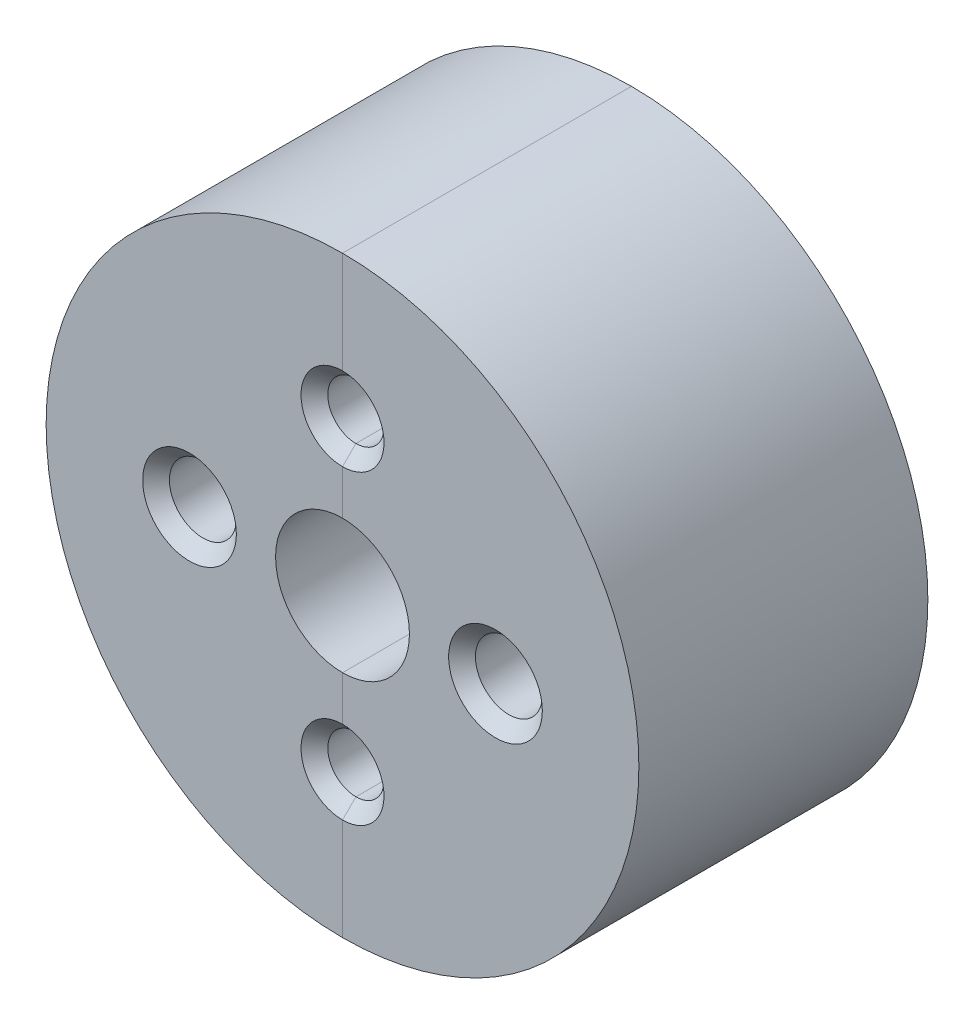
SolidWorks part; units mm, degrees
material "AISI 8620, Normalized steel"
ref_plane "Front Plane" through (0, 0, 0) normal (0, 0, 1) x (1, 0, 0)
ref_plane "Top Plane" through (0, 0, 0) normal (0, 1, 0) x (1, 0, 0)
ref_plane "Right Plane" through (0, 0, 0) normal (1, 0, 0) x (0, 0, -1)
sketch "Sketch1" plane through (0, 0, 0) normal (0, 0, 1) x (1, 0, 0)
  circle A0 centre (0, 0) radius 22.1425
  dimension "D1" = 44.2849
extrude "Boss-Extrude1" add sketch "Sketch1" along normal blind 21.59 contours A0
chamfer "Chamfer1" [suppressed] distance 2 angle 45
sketch "Sketch2" plane through (0, 0, 0) normal (0, 0, -1) x (-1, 0, 0)
  circle A0 centre (0, 0) radius 22.1425 construction
  circle A1 centre (0, 0) radius 22.1425
sketch "Sketch4" plane through (0, 0, 0) normal (0, 0, -1) x (-1, 0, 0)
  circle A0 centre (0, 0) radius 16.129
  dimension "D1" = 32.258
extrude "Boss-Extrude2" add sketch "Sketch4" along normal blind 2
sketch "Sketch6" plane through (0, 0, 21.59) normal (0, 0, 1) x (1, 0, 0)
  circle A0 centre (0, 0) radius 5
  dimension "D1" = 10
extrude "Cut-Extrude1" cut sketch "Sketch6" against normal through all
sketch "Sketch8" plane through (0, 0, -2) normal (0, 0, -1) x (-1, 0, 0)
  circle A0 centre (0, 0) radius 11.43 construction
  circle A1 centre (0, 11.43) radius 2.5
  circle A2 centre (11.43, 0) radius 2.5
  circle A3 centre (0, -11.43) radius 2.5
  circle A4 centre (-11.43, 0) radius 2.5
  point P14 (0, 0)
  dimension "D1" = 22.86
  dimension "D2" = 4
sketch "Sketch9" plane through (0, 0, 0) normal (0, 1, 0) x (1, 0, 0)
  line L0 (-22.1425, -10.795) -> (22.1424, -10.795) construction
  line L1 (-22.1425, 0) -> (-22.1425, -21.59) construction
  line L2 (22.1425, -21.59) -> (22.1425, 0) construction
  circle A0 centre (0, -10) radius 2.5
sketch "Sketch10" plane through (0, 0, 21.59) normal (0, 0, 1) x (1, 0, 0)
  circle A0 centre (0, 0) radius 9
  dimension "D1" = 18
extrude "Cut-Extrude4" [suppressed] cut sketch "Sketch10" against normal blind 1.5
chamfer "Chamfer2" distance 0.5 angle 45 1 edges at (-16.129, 0, -2)
hole_wizard "M5x0.8 Tapped Hole1" positions "3DSketch1" profile "Sketch11" tap size "M5x0.8" standard "ANSI Metric" end condition through all
sketch3d "3DSketch1"
  point P0 (0, 11.43, -2)
sketch "Sketch11" plane through (0, 11.43, -2) normal (1, 0, 0) x (0, 1, 0)
  line L0 (0, 0) -> (0, 23.59)
  line L1 (0, 23.59) -> (2.1, 23.59)
  line L2 (2.1, 23.59) -> (2.1, 0)
  line L5 (2.1, 0) -> (0, 0)
  line L11 (0, -6.35) -> (0, 107.95) construction
  dimension "Thru Tap Drill Dia." = 4.2
  dimension "Thru Tap Drill Depth" = 23.59
cosmetic thread "Hole Thread1" parameters "D2"=5
pattern_circular "CirPattern1" count 2 over 360 about axis through (0, 0, 0) along (0, 0, 1) of "M5x0.8 Tapped Hole1"
hole_wizard "Ø5.0mm Transitional Dowel Hole1" positions "3DSketch2" profile "Sketch12" hole size "Ø5.0" standard "ANSI Metric" end condition through all
sketch3d "3DSketch2"
  point P0 (-11.43, 0, -2)
sketch "Sketch12" plane through (-11.43, 0, -2) normal (1, 0, 0) x (0, 1, 0)
  line L0 (0, 0) -> (0, 23.59)
  line L1 (0, 23.59) -> (2.5, 23.59)
  line L2 (2.5, 23.59) -> (2.5, 0)
  line L5 (2.5, 0) -> (0, 0)
  line L11 (0, -6.35) -> (0, 107.95) construction
  dimension "Thru Hole Dia." = 5
  dimension "Thru Hole Depth" = 23.59
pattern_circular "CirPattern2" count 2 over 360 about axis through (0, 0, 0) along (0, 0, 1) of "Ø5.0mm Transitional Dowel Hole1"
chamfer "Chamfer3" distance 1 angle 45 4 edges at (8.93, 0, 21.59) (-2.1, -11.43, 21.59) (-13.93, 0, 21.59) (-2.1, 11.43, 21.59)
hole_wizard "1/4-20 Tapped Hole1" positions "3DSketch3" profile "Sketch14" tap size "1/4-20" standard "ANSI Inch"
sketch3d "3DSketch3"
  point P0 (0.075, -22.1423, 10.4201)
sketch "Sketch14" plane through (0.075, -22.1423, 10.4201) normal (0, 0, 1) x (1, 0.0034, 0)
  line L0 (0, 0) -> (0, 20.5838)
  line L1 (0, 20.5838) -> (2.5527, 19.05)
  line L2 (2.5527, 19.05) -> (2.5527, 0)
  line L5 (2.5527, 0) -> (0, 0)
  line L10 (0, 20.5838) -> (-2.5527, 19.05) construction
  line L11 (0, -6.35) -> (0, 107.95) construction
  dimension "Tap Drill Dia." = 5.1054
  dimension "Tap Drill Depth" = 19.05
  dimension "Drill Angle" = 118
cosmetic thread "Hole Thread3" parameters "D1"=17.8432, "D2"=6.35
sketch "Sketch17" plane through (0, 0, 21.59) normal (0, 0, 1) x (1, 0, 0)
  line L0 (0, 22.1425) -> (0, -22.1425)
  circle A0 centre (0, 0) radius 22.1425 construction
split "Split2" trim tools "Sketch17" bodies to split 121 resulting bodies 126 127
sketch "Sketch18" [suppressed] plane through (0, 0, 21.59) normal (0, 0, 1) x (1, 0, 0)
  circle A0 centre (0, 0) radius 23.5966
  arc A1 (0, 22.1425) -> (0, -22.1425) centre (0, 0) ccw construction
  arc A2 (0, -22.1425) -> (0, 22.1425) centre (0, 0) ccw construction
  arc A3 (0, 22.1425) -> (0, -22.1425) centre (0, 0) ccw
  arc A4 (0, -22.1425) -> (0, 22.1425) centre (0, 0) ccw
  dimension "D1" = 47.1932
extrude "Boss-Extrude3" [suppressed] add sketch "Sketch18" against normal blind 21.59
